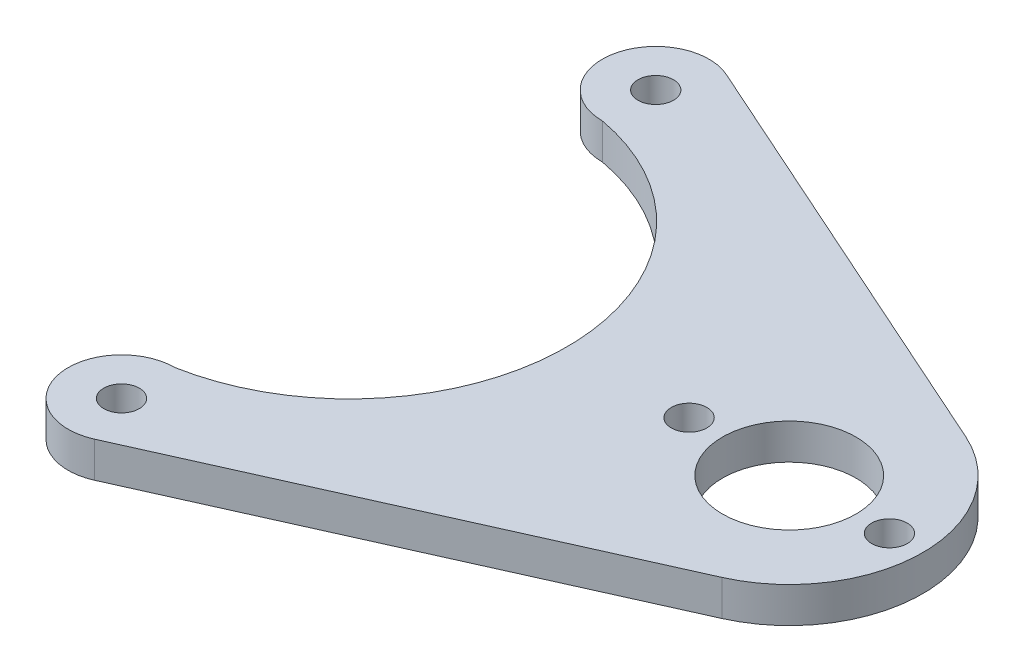
SolidWorks part; units mm, degrees
material "AISI 1020"
ref_plane "Front Plane" through (0, 0, 0) normal (0, 0, 1) x (1, 0, 0)
ref_plane "Top Plane" through (0, 0, 0) normal (0, 1, 0) x (1, 0, 0)
ref_plane "Right Plane" through (0, 0, 0) normal (1, 0, 0) x (0, 0, -1)
sketch "Sketch2" plane through (0, 0, 0) normal (0, 1, 0) x (1, 0, 0)
  line L0 (-90, 60) -> (-90, -60) construction
  line L1 (0, 0) -> (-90, 0) construction
  line L2 (0, 0) -> (-50, 0) construction
  circle A0 centre (0, 0) radius 22.5 construction
  circle A1 centre (22.5, 0) radius 4
  circle A2 centre (-22.5, 0) radius 4
  point P11 (-90, 0)
  dimension "D1" = 45
  dimension "D2" = 8
  dimension "D3" = 90
  dimension "D4" = 120
  dimension "D5" = 40
sketch "Sketch3" plane through (0, 0, 0) normal (0, 1, 0) x (1, 0, 0)
  line L0 (-85.0979, 70.9531) -> (12.2551, 27.3827)
  line L1 (12.2551, -27.3827) -> (-85.0979, -70.9531)
  circle A0 centre (-90, 60) radius 4
  circle A1 centre (-90, -60) radius 4
  circle A2 centre (22.5, 0) radius 4 construction
  circle A3 centre (-22.5, 0) radius 4 construction
  circle A4 centre (22.5, 0) radius 4
  circle A5 centre (-22.5, 0) radius 4
  circle A6 centre (0, 0) radius 15
  arc A7 (12.2551, -27.3827) -> (12.2551, 27.3827) centre (0, 0) ccw
  arc A8 (-85.0979, 70.9531) -> (-90, 48) centre (-90, 60) ccw
  arc A9 (-90, -48) -> (-85.0979, -70.9531) centre (-90, -60) ccw
  arc A10 (-90, 48) -> (-90, -48) centre (-98.8, 0) cw
  circle A12 centre (-90, 60) radius 12 construction
  circle A13 centre (-90, -60) radius 12 construction
  point P17 (-81, -60)
  point P27 (-81, 60)
  dimension "D1" = 60
  dimension "D2" = 30
  dimension "D3" = 8
extrude "Boss-Extrude1" add sketch "Sketch3" along normal blind 8
